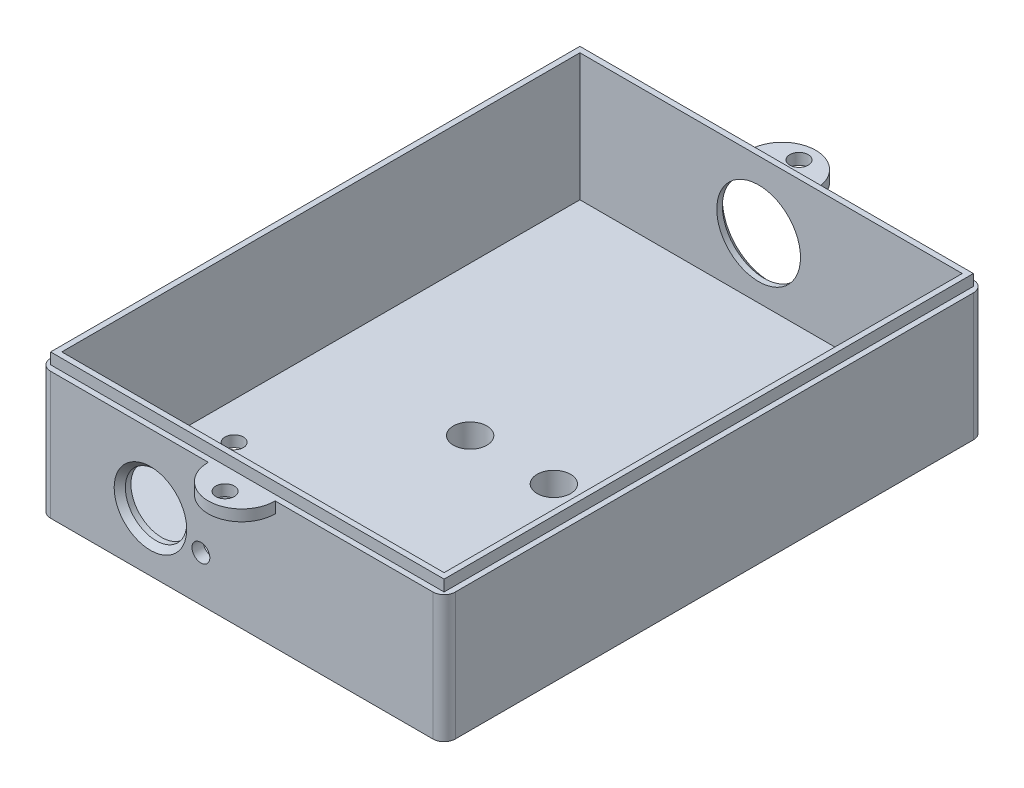
SolidWorks part; units mm, degrees
ref_plane "Front Plane" through (0, 0, 0) normal (1, 0, 0) x (0, 1, 0)
ref_plane "Top Plane" through (0, 0, 0) normal (0, 0, 1) x (0, 1, 0)
ref_plane "Right Plane" through (0, 0, 0) normal (0, 1, 0) x (-1, 0, 0)
sketch "Sketch1" plane through (0, 0, 0) normal (0, 1, 0) x (1, 0, 0)
  line L0 (80.8703, 33.3957) -> (153.3703, 33.3957)
  line L1 (153.3703, 33.3957) -> (153.3703, -63.4327)
  line L2 (153.3703, -63.4327) -> (80.8703, -63.4327)
  line L3 (80.8703, -63.4327) -> (80.8703, 33.3957)
extrude "Boss-Extrude1" add sketch "Sketch1" along normal blind 18 and the other way offset from surface (12.8155 mm away) 0.5 contours L0 L1 L2 L3
shell "Shell1" thickness 2
sketch "Sketch2" plane through (0, 0, -33.3957) normal (0, 0, -1) x (-1, 0, 0)
  line L2 (-80.8703, -12.8155) -> (-153.3703, -12.8155) construction
  line L3 (-153.3703, -12.8155) -> (-153.3703, 18) construction
  circle A0 centre (-114.8937, -0.0005) radius 7.5
  dimension "D1" = 15
  dimension "D2" = 12.815
  dimension "D3" = 38.4765
extrude "Cut-Extrude1" cut sketch "Sketch2" against normal up to surface (2 mm away) up to face at (117.1203, 2.5923, -31.3957)
chamfer "Chamfer1" distance 1 angle 45 1 edges at (107.3937, -0.0005, -33.3957)
sketch "Sketch5" plane through (0, 0, 63.4327) normal (0, 0, 1) x (1, 0, 0)
  line L0 (153.3703, -12.8155) -> (80.8703, -12.8155) construction
  circle A0 centre (100.7621, -2.3405) radius 5.5
  dimension "D1" = 11
  dimension "D2" = 10.475
extrude "Cut-Extrude2" cut sketch "Sketch5" against normal up to surface (2 mm away) up to face at (117.1203, 2.5923, 61.4327)
chamfer "Chamfer2" distance 1 angle 45 1 edges at (106.2621, -2.3405, 63.4327)
sketch "Sketch8" plane through (0, 18, 0) normal (0, 1, 0) x (1, 0, 0)
  line L1 (80.8703, 33.3957) -> (153.3703, 33.3957)
  line L2 (80.8703, 33.3957) -> (80.8703, -63.4327)
  line L3 (80.8703, -63.4327) -> (153.3703, -63.4327)
  line L4 (153.3703, 33.3957) -> (153.3703, -63.4327)
extrude "Cut-Extrude5" cut sketch "Sketch8" against normal blind 8
sketch "Sketch10" plane through (0, 0, 0) normal (0, 1, 0) x (1, 0, 0)
  line L0 (82.8703, 31.3957) -> (151.3703, 31.3957)
  line L1 (151.3703, 31.3957) -> (151.3703, -61.4327)
  line L2 (151.3703, -61.4327) -> (82.8703, -61.4327)
  line L3 (82.8703, -61.4327) -> (82.8703, 31.3957)
  line L4 (81.8703, -62.4327) -> (81.8703, 32.3957)
  line L5 (81.8703, 32.3957) -> (152.3703, 32.3957)
  line L6 (152.3703, 32.3957) -> (152.3703, -62.4327)
  line L7 (152.3703, -62.4327) -> (81.8703, -62.4327)
  dimension "D1" = 1
extrude "Boss-Extrude3" add sketch "Sketch10" along normal blind 2 from surface at 10 starting at face at (117.1203, 10, 15.0185)
sketch "Sketch12" plane through (0, 0, 63.4327) normal (0, 0, 1) x (1, 0, 0)
  circle A0 centre (109.7963, -4.6802) radius 1.6
  dimension "D1" = 3.2
extrude "Cut-Extrude6" cut sketch "Sketch12" against normal up to surface (2 mm away)
fillet "Fillet1" radius 2 4 edges at (80.8703, -1.4077, -33.3957) (80.8703, -1.4077, 63.4327) (153.3703, -1.4077, -33.3957) (153.3703, -1.4077, 63.4327)
sketch "Sketch13" plane through (0, 0, 0) normal (0, 1, 0) x (1, 0, 0)
  line L0 (82.8703, -63.4327) -> (151.3703, -63.4327) construction
  line L1 (111.1203, -63.4327) -> (123.1203, -63.4327)
  circle A0 centre (117.1203, -66.4327) radius 1.65
  arc A1 (111.1203, -63.4327) -> (123.1203, -63.4327) centre (117.1203, -63.4327) ccw
  dimension "D1" = 3.3
extrude "Boss-Extrude4" add sketch "Sketch13" against normal blind 2 from surface at 10 starting at face at (117.1203, 10, 15.0185)
ref_plane "Plane2" through (0, 10, 0) normal (0, 1, 0) x (1, 0, 0)
sketch "Sketch16" plane through (0, 10, 0) normal (0, 1, 0) x (1, 0, 0)
  line L0 (151.3703, 33.3957) -> (82.8703, 33.3957) construction
  line L1 (111.1203, 33.3957) -> (123.1203, 33.3957)
  circle A0 centre (117.1203, 36.3957) radius 1.65
  arc A1 (111.1203, 33.3957) -> (123.1203, 33.3957) centre (117.1203, 33.3957) cw
  arc A2 (123.1203, 33.3957) -> (111.1203, 33.3957) centre (117.1203, 33.3957) ccw construction
extrude "Boss-Extrude5" add sketch "Sketch16" against normal blind 2
sketch "Sketch17" plane through (0, 0, 0) normal (0, 1, 0) x (1, 0, 0)
  circle A0 centre (137.7852, -38.4627) radius 1.65
  circle A1 centre (89.5252, -37.1927) radius 1.65
  dimension "D1" = 3.3
  dimension "D2" = 3.3
extrude "Cut-Extrude8" cut sketch "Sketch17" against normal up to surface (12.8155 mm away) up to face at (117.1203, -12.8155, 15.0185)
sketch "Sketch19" plane through (0, -12.8155, 0) normal (0, -1, 0) x (1, 0, 0)
  line L0 (80.8703, 15.0185) -> (153.3703, 15.0185) construction
  line L1 (94.6367, 2.8399) -> (139.6038, 2.8399)
  line L2 (94.6367, 2.8399) -> (94.6367, 27.1971)
  line L3 (94.6367, 27.1971) -> (139.6038, 27.1971)
  line L4 (139.6038, 2.8399) -> (139.6038, 27.1971)
  line L5 (94.6367, 2.8399) -> (139.6038, 27.1971) construction
  line L6 (94.6367, 27.1971) -> (139.6038, 2.8399) construction
  line L7 (80.8703, 61.4327) -> (80.8703, -31.3957) construction
  line L8 (153.3703, -31.3957) -> (153.3703, 61.4327) construction
  line L9 (117.1203, 63.4327) -> (117.1203, -33.3957) construction
  line L10 (151.3703, 63.4327) -> (82.8703, 63.4327) construction
  line L11 (82.8703, -33.3957) -> (151.3703, -33.3957) construction
  point P0 (117.1203, 15.0185)
extrude "Boss-Extrude6" add sketch "Sketch19" along normal blind 12
sketch "Sketch18" plane through (0, 0, 0) normal (0, 1, 0) x (1, 0, 0)
  line L0 (117.1203, -63.4327) -> (117.1203, 31.3957) construction
  line L1 (151.3703, -63.4327) -> (82.8703, -63.4327) construction
  line L2 (82.8703, 31.3957) -> (151.3703, 31.3957) construction
  line L4 (80.8703, -15.0185) -> (153.3703, -15.0185) construction
  line L5 (80.8703, 33.3957) -> (80.8703, -63.4327) construction
  line L6 (153.3703, 31.3957) -> (153.3703, -61.4327) construction
  circle A0 centre (124.6203, -15.0185) radius 3
  circle A1 centre (109.6203, -15.0185) radius 3
  point P19 (117.1203, -15.0185)
  dimension "D1" = 6
  dimension "D2" = 6
  dimension "D3" = 15
  dimension "D4" = 7.5
extrude "Cut-Extrude9" cut sketch "Sketch18" against normal up to surface (14 mm away) from surface at -10.8155 up to face at (117.1203, -24.8155, 15.0185) starting at face at (137.7852, -10.8155, 36.8127)
ref_plane "Plane1" through (0, 0, 15.0185) normal (0, 0, 1) x (1, 0, 0)
mirror "Mirror1" about plane through (0, 0, 15.0185) normal (0, 0, 1) of "Boss-Extrude4"
sketch "Sketch14" plane through (0, -10.8155, 0) normal (0, 1, 0) x (1, 0, 0)
  circle A0 centre (140.5178, -46.4627) radius 1.5999
  circle A2 centre (92.2578, -45.1927) radius 1.5999
  dimension "D1" = 3.1999
extrude "Cut-Extrude7" cut sketch "Sketch14" against normal up to surface (2 mm away) up to face at (137.7852, -12.8155, 36.8127)
sketch "Sketch6" plane through (0, 0, 0) normal (0, 1, 0) x (1, 0, 0)
  circle A0 centre (130.0953, -39.9957) radius 4.75
  circle A1 centre (143.0553, -39.9327) radius 3.5
  circle A2 centre (143.0553, -32.4327) radius 3.5
  dimension "D1" = 7
  dimension "D2" = 7
  dimension "D3" = 9.5
